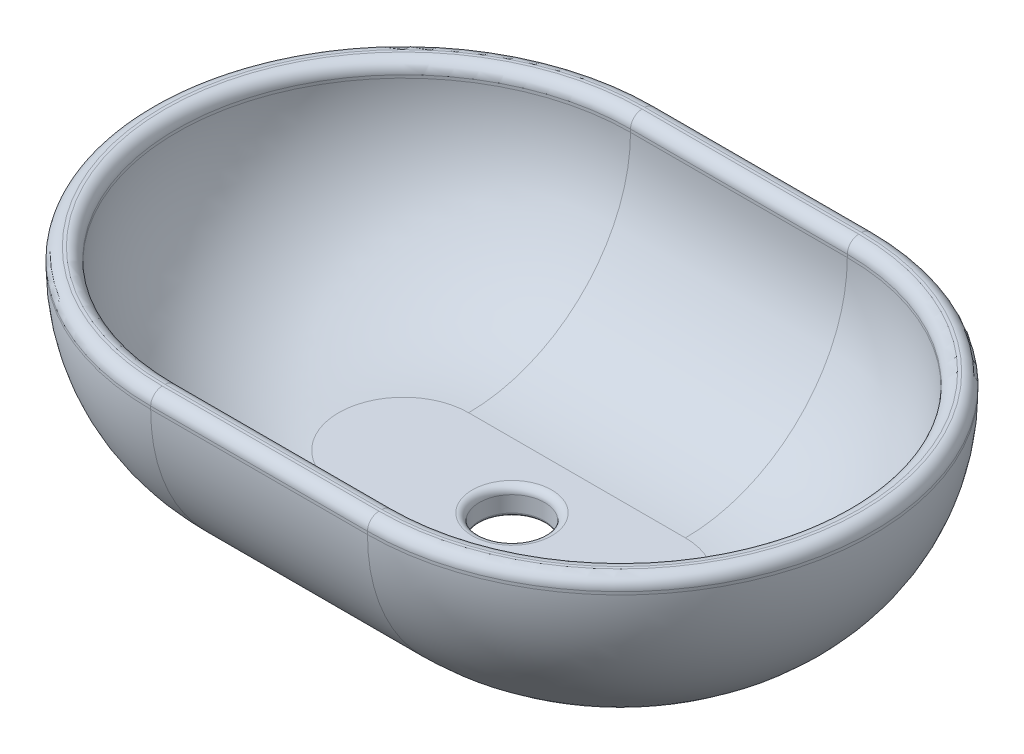
SolidWorks part; units mm, degrees
ref_plane "Front Plane" through (0, 0, 0) normal (0, 0, 1) x (1, 0, 0)
ref_plane "Top Plane" through (0, 0, 0) normal (0, 1, 0) x (1, 0, 0)
ref_plane "Right Plane" through (0, 0, 0) normal (1, 0, 0) x (0, 0, -1)
sketch "Sketch1" plane through (0, 0, 0) normal (0, 1, 0) x (1, 0, 0)
  line L0 (-75, 0) -> (75, 0) construction
  line L1 (-75, 175) -> (75, 175)
  line L2 (-75, -175) -> (75, -175)
  arc A0 (-75, 175) -> (-75, -175) centre (-75, 0) ccw
  arc A1 (75, -175) -> (75, 175) centre (75, 0) ccw
  point P3 (0, 0)
  point P8 (-250, 0)
  point P9 (250, 0)
  point P10 (0, 0)
  dimension "D3" = 175
  dimension "D1" = 350
  dimension "D2" = 500
extrude "Boss-Extrude1" add sketch "Sketch1" along normal blind 140
fillet "Fillet1" radius 130 4 edges at (-250, 0, 0) (0, 0, -175) (250, 0, 0) (0, 0, 175)
shell "Shell1" thickness 18
sketch "Sketch2" plane through (0, 18, 0) normal (0, 1, 0) x (1, 0, 0)
  circle A0 centre (0, 0) radius 22.5
  dimension "D1" = 45
extrude "Cut-Extrude1" cut sketch "Sketch2" against normal blind 140
fillet "Fillet2" radius 5 1 edges at (0, 18, 22.5)
fillet "Fillet3" radius 2 1 edges at (0, 0, 22.5)
fillet "Fillet4" radius 8 8 edges at (0, 140, -157) (232, 140, 0) (0, 140, 157) (0, 140, -175) (250, 140, 0) (0, 140, 175) (-232, 140, 0) (-250, 140, 0)
